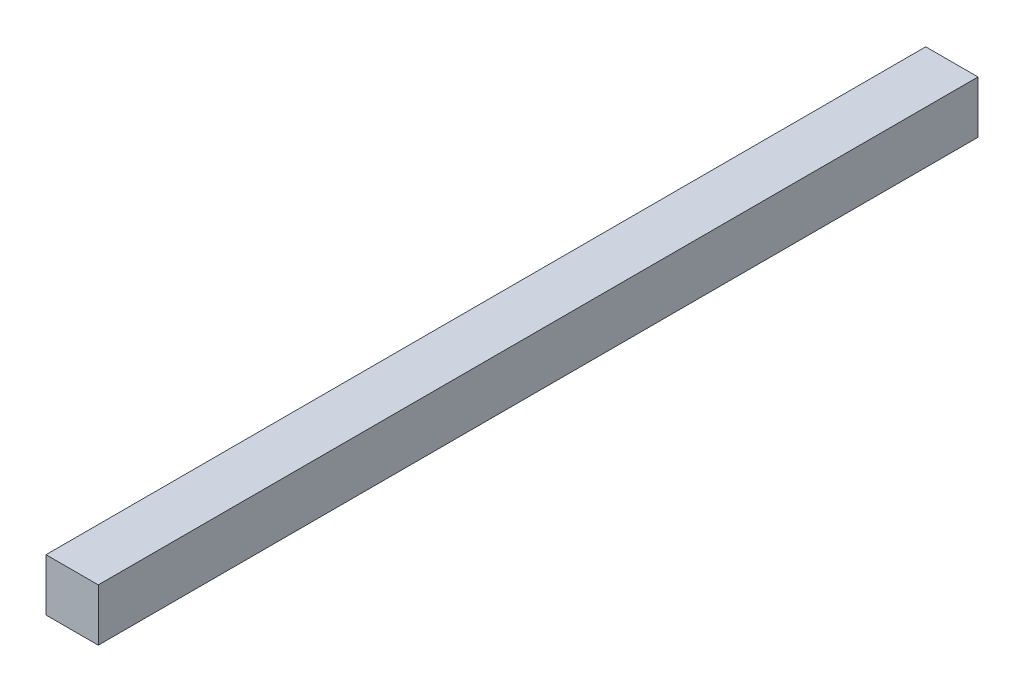
SolidWorks part; units mm, degrees
material "6061-T6 (SS)"
ref_plane "Alzado" through (0, 0, 0) normal (0, 0, 1) x (1, 0, 0)
ref_plane "Planta" through (0, 0, 0) normal (0, 1, 0) x (1, 0, 0)
ref_plane "Vista lateral" through (0, 0, 0) normal (1, 0, 0) x (0, 0, -1)
sketch "Sketch1" plane through (0, 0, 0) normal (0, 0, 1) x (1, 0, 0)
  line L1 (-6, 6) -> (6, 6)
  line L2 (-6, 6) -> (-6, -6)
  line L3 (-6, -6) -> (6, -6)
  line L4 (6, 6) -> (6, -6)
  line L5 (-6, 6) -> (6, -6) construction
  line L6 (-6, -6) -> (6, 6) construction
  point P0 (0, 0)
  dimension "D1" = 12
  dimension "D2" = 12
extrude "Boss-Extrude1" add sketch "Sketch1" along normal blind 202
